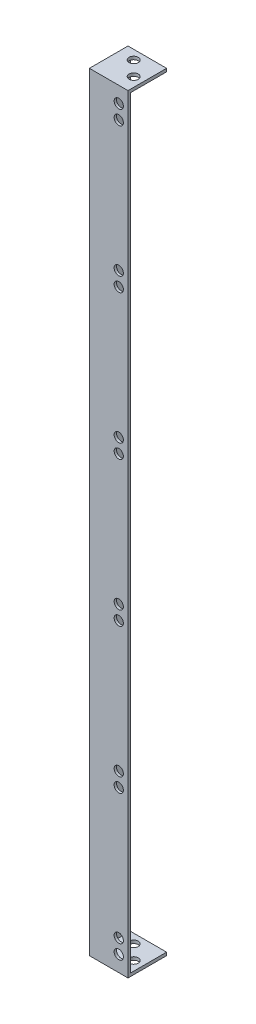
SolidWorks part; units mm, degrees
material "7075-O (SS)"
ref_plane "Front Plane" through (0, 0, 0) normal (0, 0, 1) x (1, 0, 0)
ref_plane "Top Plane" through (0, 0, 0) normal (0, 1, 0) x (1, 0, 0)
ref_plane "Right Plane" through (0, 0, 0) normal (1, 0, 0) x (0, 0, -1)
sketch "Sketch1" plane through (0, 0, 0) normal (0, 1, 0) x (1, 0, 0)
  line L0 (0, 0) -> (0, 16.3)
  line L1 (0, 16.3) -> (1, 16.3)
  line L2 (1, 16.3) -> (1, 1)
  line L3 (1, 1) -> (16.3, 1)
  line L4 (16.3, 1) -> (16.3, 0)
  line L5 (16.3, 0) -> (0, 0)
  dimension "D1" = 16.3
  dimension "D2" = 16.3
  dimension "D3" = 1
  dimension "D4" = 1
extrude "Boss-Extrude1" add sketch "Sketch1" along normal blind 327 contours L0 L1 L2 L3 L4 L5
sketch "Sketch2" plane through (0, 0, 0) normal (0, 0, 1) x (1, 0, 0)
  line L0 (16.3, 327) -> (16.3, 0) construction
  line L1 (16.3, 327) -> (0, 327) construction
  circle A0 centre (12.4, 319) radius 1.95
  circle A1 centre (12.4, 313) radius 1.95
  circle A2 centre (12.4, 258) radius 1.95
  circle A3 centre (12.4, 252) radius 1.95
  circle A4 centre (12.4, 197) radius 1.95
  circle A5 centre (12.4, 191) radius 1.95
  circle A6 centre (12.4, 136) radius 1.95
  circle A7 centre (12.4, 130) radius 1.95
  circle A8 centre (12.4, 75) radius 1.95
  circle A9 centre (12.4, 69) radius 1.95
  circle A10 centre (12.4, 14) radius 1.95
  circle A11 centre (12.4, 8) radius 1.95
  dimension "D1" = 3.9
  dimension "D2" = 3.9
  dimension "D3" = 3.9
  dimension "D4" = 3.9
  dimension "D5" = 6
  dimension "D6" = 8
  dimension "D7" = 6
extrude "Cut-Extrude1" cut sketch "Sketch2" against normal blind 2 contours A4 | A5 | A6 | A7 | A8 | A9 | A10 | A11 | A0 | A1 | A2 | A3
sketch "Sketch3" plane through (0, 0, 0) normal (-1, 0, 0) x (0, 0, 1)
  line L0 (-16.3, 327) -> (-16.3, 0) construction
  line L1 (0, 327) -> (-16.3, 327) construction
  circle A0 centre (-12.4, 319) radius 1.95
  circle A1 centre (-12.4, 313) radius 1.95
  circle A2 centre (-12.4, 258) radius 1.95
  circle A3 centre (-12.4, 252) radius 1.95
  circle A4 centre (-12.4, 197) radius 1.95
  circle A5 centre (-12.4, 191) radius 1.95
  circle A6 centre (-12.4, 136) radius 1.95
  circle A7 centre (-12.4, 130) radius 1.95
  circle A8 centre (-12.4, 75) radius 1.95
  circle A9 centre (-12.4, 69) radius 1.95
  circle A10 centre (-12.4, 14) radius 1.95
  circle A11 centre (-12.4, 8) radius 1.95
  dimension "D1" = 3.9
  dimension "D2" = 3.9
  dimension "D3" = 6
  dimension "D4" = 0
  dimension "D5" = 3.9
  dimension "D6" = 8
  dimension "D7" = 6
extrude "Cut-Extrude2" cut sketch "Sketch3" against normal blind 2 contours A1 | A2 | A3 | A4 | A5 | A6 | A7 | A8 | A9 | A11 | A10 | A0
sketch "Sketch5" plane through (0, 0, 0) normal (-1, 0, 0) x (0, 0, 1)
  line L0 (0, 327) -> (0, 0) construction
  line L1 (-16.3, 327) -> (0, 327)
  line L2 (-16.3, 327) -> (-16.3, 325.7)
  line L3 (-16.3, 325.7) -> (0, 325.7)
  line L4 (0, 327) -> (0, 325.7)
  line L5 (-16.3, 327) -> (-16.3, 0) construction
  line L6 (-16.3, 0) -> (0, 0)
  line L7 (-16.3, 0) -> (-16.3, 1.3)
  line L8 (-16.3, 1.3) -> (0, 1.3)
  line L9 (0, 0) -> (0, 1.3)
  line L10 (0, 0) -> (-16.3, 0) construction
  line M17 (-16.3, 0) -> (0, 0)
  line M18 (0, 0) -> (0, 327)
  line M20 (-16.3, 327) -> (-16.3, 0)
  dimension "D1" = 1.3
  dimension "D2" = 1.3
extrude "Cut-Extrude4" cut sketch "Sketch5" against normal blind 20 contours L8 M20 M17 M18 | L1 L4 L3 L2
sketch "Sketch6" plane through (0, 325.7, 0) normal (0, 1, 0) x (1, 0, 0)
  line L1 (0, 16.3) -> (16.3, 16.3)
  line L2 (0, 16.3) -> (0, 0)
  line L3 (0, 0) -> (16.3, 0)
  line L4 (16.3, 16.3) -> (16.3, 0)
extrude "Boss-Extrude3" add sketch "Sketch6" against normal blind 1.3
sketch "Sketch7" plane through (0, 1.3, 0) normal (0, -1, 0) x (1, 0, 0)
  line L1 (0, -16.3) -> (16.3, -16.3)
  line L2 (0, -16.3) -> (0, 0)
  line L3 (0, 0) -> (16.3, 0)
  line L4 (16.3, -16.3) -> (16.3, 0)
extrude "Boss-Extrude4" add sketch "Sketch7" against normal blind 1.3
sketch "Sketch8" plane through (0, 1.3, 0) normal (0, -1, 0) x (1, 0, 0)
  line L0 (16.3, 0) -> (0, 0) construction
  line L1 (0, -16.3) -> (0, 0) construction
  line L2 (16.3, -16.3) -> (0, -16.3) construction
  line L3 (16.3, 0) -> (16.3, -16.3) construction
  circle A0 centre (12.4, -6.3) radius 1.95
  circle A1 centre (6.3, -12.4) radius 1.95
  dimension "D1" = 3.9
  dimension "D2" = 3.9
  dimension "D3" = 6.3
  dimension "D4" = 6.3
  dimension "D5" = 3.9
  dimension "D6" = 3.9
extrude "Cut-Extrude7" cut sketch "Sketch8" against normal blind 350
